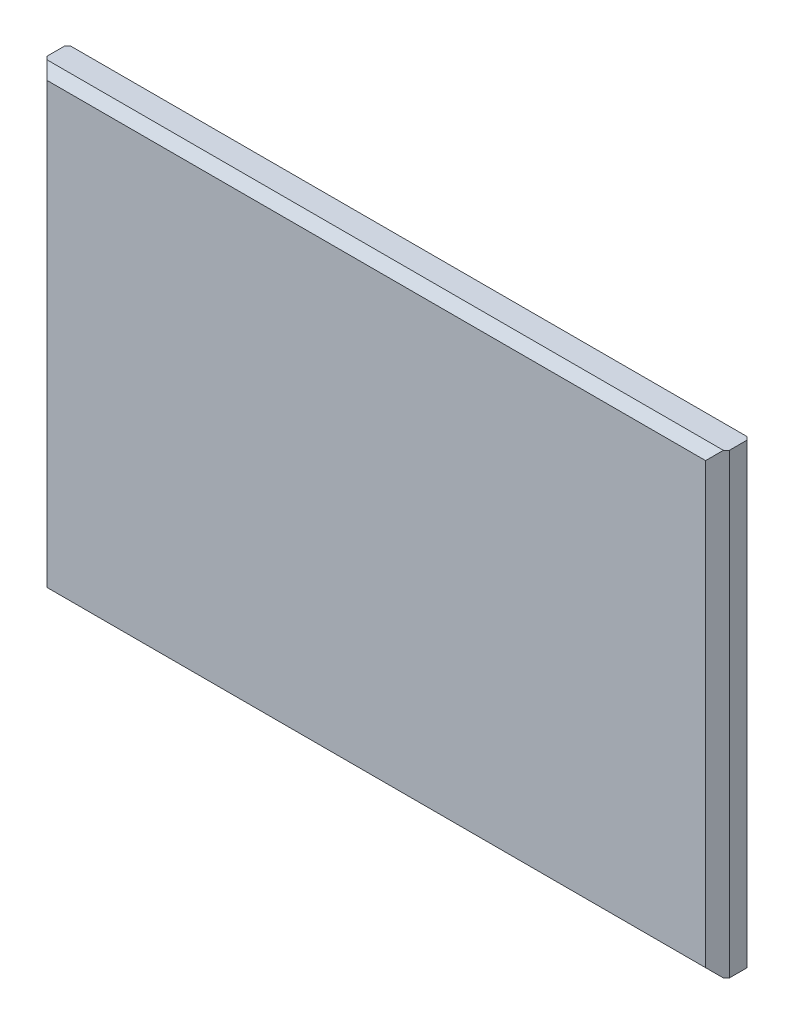
SolidWorks part; units mm, degrees
ref_plane "Front" through (0, 0, 0) normal (0, 0, 1) x (1, 0, 0)
ref_plane "Top" through (0, 0, 0) normal (0, 1, 0) x (1, 0, 0)
ref_plane "Right" through (0, 0, 0) normal (1, 0, 0) x (0, 0, -1)
sketch "Sketch3" plane through (0, 0, 0) normal (0, 0, 1) x (1, 0, 0)
  line L1 (-14.605, 9.779) -> (14.605, 9.779)
  line L2 (-14.605, 9.779) -> (-14.605, -9.779)
  line L3 (-14.605, -9.779) -> (14.605, -9.779)
  line L4 (14.605, 9.779) -> (14.605, -9.779)
  line L5 (-14.605, 9.779) -> (14.605, -9.779) construction
  line L6 (-14.605, -9.779) -> (14.605, 9.779) construction
  point P0 (0, 0)
  dimension "D1" = 29.21
  dimension "D2" = 19.558
extrude "Boss-Extrude1" add sketch "Sketch3" along normal blind 1.778
chamfer "Chamfer1" distance 0.381 angle 45 4 edges at (0, -9.779, 1.778) (0, -9.779, 0) (0, 9.779, 0) (0, 9.779, 1.778)
chamfer "Chamfer2" distance 0.508 angle 45 4 edges at (14.605, 0, 1.778) (14.605, 0, 0) (-14.605, 0, 0) (-14.605, 0, 1.778)
